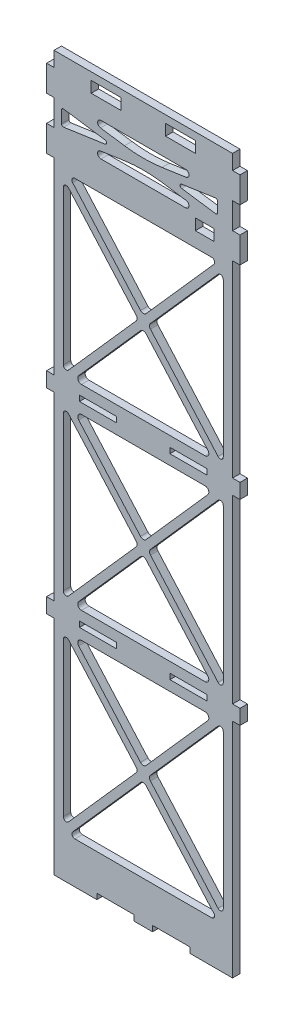
SolidWorks part; units mm, degrees
ref_plane "前视基准面" through (0, 0, 0) normal (0, 0, 1) x (1, 0, 0)
ref_plane "上视基准面" through (0, 0, 0) normal (0, 1, 0) x (1, 0, 0)
ref_plane "右视基准面" through (0, 0, 0) normal (1, 0, 0) x (0, 0, -1)
other "Configuration Table"
sketch "草图1" plane through (0, 0, 0) normal (0, 0, 1) x (1, 0, 0)
  line L0 (2263.2404, 1874.8927) -> (2311.2404, 1874.8927)
  line L1 (2313.2404, 1870.8927) -> (2313.2404, 1863.8927)
  line L2 (2313.2404, 1856.8927) -> (2313.2404, 1849.8927)
  line L3 (2313.2404, 1799.2927) -> (2313.2404, 1795.2927)
  line L4 (2313.2404, 1746.6927) -> (2313.2404, 1742.6927)
  line L5 (2263.2404, 1682.8927) -> (2274.7404, 1682.8927)
  line L6 (2284.7404, 1682.8927) -> (2289.7404, 1682.8927)
  line L7 (2299.7404, 1682.8927) -> (2311.2404, 1682.8927)
  line L8 (2261.2404, 1870.8927) -> (2261.2404, 1863.8927)
  line L9 (2261.2404, 1856.8927) -> (2261.2404, 1849.8927)
  line L10 (2311.2404, 1874.8927) -> (2311.2404, 1870.8927)
  line L11 (2311.2404, 1863.8927) -> (2311.2404, 1856.8927)
  line L12 (2313.2404, 1870.8927) -> (2311.2404, 1870.8927)
  line L13 (2313.2404, 1863.8927) -> (2311.2404, 1863.8927)
  line L14 (2313.2404, 1856.8927) -> (2311.2404, 1856.8927)
  line L15 (2313.2404, 1849.8927) -> (2311.2404, 1849.8927)
  line L16 (2313.2404, 1795.2927) -> (2311.2404, 1795.2927)
  line L17 (2311.2404, 1799.2927) -> (2313.2404, 1799.2927)
  line L18 (2311.2404, 1849.8927) -> (2311.2404, 1799.2927)
  line L19 (2313.2404, 1746.6927) -> (2311.2404, 1746.6927)
  line L20 (2311.2404, 1742.6927) -> (2313.2404, 1742.6927)
  line L21 (2311.2404, 1795.2927) -> (2311.2404, 1746.6927)
  line L22 (2311.2404, 1742.6927) -> (2311.2404, 1682.8927)
  line L23 (2263.2404, 1874.8927) -> (2263.2404, 1870.8927)
  line L24 (2263.2404, 1870.8927) -> (2261.2404, 1870.8927)
  line L25 (2261.2404, 1870.8927) -> (2261.2404, 1863.8927)
  line L26 (2261.2404, 1799.2927) -> (2261.2404, 1795.2927)
  line L27 (2261.2404, 1746.6927) -> (2261.2404, 1742.6927)
  line L28 (2263.2404, 1863.8927) -> (2263.2404, 1856.8927)
  line L29 (2261.2404, 1863.8927) -> (2263.2404, 1863.8927)
  line L30 (2261.2404, 1856.8927) -> (2263.2404, 1856.8927)
  line L31 (2261.2404, 1849.8927) -> (2263.2404, 1849.8927)
  line L32 (2261.2404, 1795.2927) -> (2263.2404, 1795.2927)
  line L33 (2263.2404, 1799.2927) -> (2261.2404, 1799.2927)
  line L34 (2263.2404, 1849.8927) -> (2263.2404, 1799.2927)
  line L35 (2261.2404, 1746.6927) -> (2263.2404, 1746.6927)
  line L36 (2263.2404, 1742.6927) -> (2261.2404, 1742.6927)
  line L37 (2263.2404, 1795.2927) -> (2263.2404, 1746.6927)
  line L38 (2263.2404, 1742.6927) -> (2263.2404, 1682.8927)
  line L39 (2305.6291, 1847.8927) -> (2287.2404, 1847.8927)
  line L40 (2306.2404, 1854.8927) -> (2301.2404, 1854.8927)
  line L41 (2306.2404, 1851.8927) -> (2301.2404, 1851.8927)
  line L42 (2268.8516, 1847.8927) -> (2305.6291, 1847.8927)
  line L43 (2268.8516, 1847.8927) -> (2275.4082, 1847.8927)
  line L44 (2299.0725, 1847.8927) -> (2305.6291, 1847.8927)
  line L45 (2305.3412, 1842.5418) -> (2289.1619, 1824.2554)
  line L46 (2286.4914, 1821.2371) -> (2269.8738, 1802.4554)
  line L47 (2306.2283, 1846.5626) -> (2290.985, 1829.3342)
  line L48 (2285.3188, 1822.9301) -> (2269.1395, 1804.6437)
  line L49 (2269.1395, 1842.5418) -> (2285.3188, 1824.2554)
  line L50 (2287.9893, 1821.2371) -> (2304.6069, 1802.4554)
  line L51 (2268.2524, 1846.5626) -> (2283.4957, 1829.3342)
  line L52 (2289.1619, 1822.9301) -> (2305.3412, 1804.6437)
  line L53 (2290.985, 1829.3342) -> (2290.1395, 1828.3785)
  line L54 (2283.4957, 1829.3342) -> (2284.3412, 1828.3785)
  line L55 (2290.1395, 1828.3785) -> (2287.9893, 1825.9483)
  line L56 (2286.4914, 1825.9483) -> (2284.3412, 1828.3785)
  line L57 (2265.7404, 1823.5927) -> (2265.7404, 1844.2721)
  line L58 (2269.1395, 1842.5418) -> (2267.1395, 1844.8022)
  line L59 (2265.7404, 1823.5927) -> (2265.7404, 1802.9133)
  line L60 (2269.1395, 1804.6437) -> (2267.1395, 1802.3832)
  line L61 (2308.7404, 1823.5927) -> (2308.7404, 1844.2721)
  line L62 (2308.7404, 1823.5927) -> (2308.7404, 1802.9133)
  line L63 (2305.3412, 1842.5418) -> (2307.3412, 1844.8022)
  line L64 (2305.3412, 1804.6437) -> (2307.3412, 1802.3832)
  line L65 (2294.3985, 1796.5427) -> (2294.3985, 1797.2927)
  line L66 (2294.3985, 1797.2927) -> (2294.3985, 1798.0427)
  line L67 (2304.3985, 1798.0427) -> (2304.3985, 1796.5427)
  line L68 (2294.3985, 1797.2927) -> (2294.3985, 1798.0427)
  line L69 (2294.3985, 1798.0427) -> (2304.3985, 1798.0427)
  line L70 (2294.3985, 1796.5427) -> (2304.3985, 1796.5427)
  line L71 (2280.0822, 1796.5427) -> (2280.0822, 1797.2927)
  line L72 (2280.0822, 1797.2927) -> (2280.0822, 1798.0427)
  line L73 (2270.0822, 1798.0427) -> (2270.0822, 1796.5427)
  line L74 (2280.0822, 1797.2927) -> (2280.0822, 1798.0427)
  line L75 (2280.0822, 1798.0427) -> (2270.0822, 1798.0427)
  line L76 (2280.0822, 1796.5427) -> (2270.0822, 1796.5427)
  line L77 (2294.3985, 1798.0427) -> (2294.3985, 1797.2927)
  line L78 (2305.3412, 1789.9418) -> (2289.1619, 1771.6554)
  line L79 (2286.4914, 1768.6371) -> (2269.8738, 1749.8554)
  line L80 (2304.6069, 1792.1301) -> (2290.985, 1776.7342)
  line L81 (2285.3188, 1770.3301) -> (2269.1395, 1752.0437)
  line L82 (2269.1395, 1789.9418) -> (2285.3188, 1771.6554)
  line L83 (2287.9893, 1768.6371) -> (2304.6069, 1749.8554)
  line L84 (2269.8738, 1792.1301) -> (2283.4957, 1776.7342)
  line L85 (2289.1619, 1770.3301) -> (2305.3412, 1752.0437)
  line L86 (2290.985, 1776.7342) -> (2290.1395, 1775.7785)
  line L87 (2283.4957, 1776.7342) -> (2284.3412, 1775.7785)
  line L88 (2290.1395, 1775.7785) -> (2287.9893, 1773.3483)
  line L89 (2286.4914, 1773.3483) -> (2284.3412, 1775.7785)
  line L90 (2265.7404, 1770.9927) -> (2265.7404, 1791.6721)
  line L91 (2269.1395, 1789.9418) -> (2267.1395, 1792.2022)
  line L92 (2265.7404, 1770.9927) -> (2265.7404, 1750.3133)
  line L93 (2269.1395, 1752.0437) -> (2267.1395, 1749.7832)
  line L94 (2308.7404, 1770.9927) -> (2308.7404, 1791.6721)
  line L95 (2308.7404, 1770.9927) -> (2308.7404, 1750.3133)
  line L96 (2305.3412, 1789.9418) -> (2307.3412, 1792.2022)
  line L97 (2305.3412, 1752.0437) -> (2307.3412, 1749.7832)
  line L98 (2294.3985, 1745.4427) -> (2294.3985, 1744.6927)
  line L99 (2294.3985, 1744.6927) -> (2294.3985, 1743.9427)
  line L100 (2304.3985, 1743.9427) -> (2304.3985, 1745.4427)
  line L101 (2294.3985, 1744.6927) -> (2294.3985, 1743.9427)
  line L102 (2294.3985, 1743.9427) -> (2304.3985, 1743.9427)
  line L103 (2294.3985, 1745.4427) -> (2304.3985, 1745.4427)
  line L104 (2280.0822, 1745.4427) -> (2280.0822, 1744.6927)
  line L105 (2280.0822, 1744.6927) -> (2280.0822, 1743.9427)
  line L106 (2270.0822, 1743.9427) -> (2270.0822, 1745.4427)
  line L107 (2280.0822, 1744.6927) -> (2280.0822, 1743.9427)
  line L108 (2280.0822, 1743.9427) -> (2270.0822, 1743.9427)
  line L109 (2280.0822, 1745.4427) -> (2270.0822, 1745.4427)
  line L110 (2294.3985, 1743.9427) -> (2294.3985, 1744.6927)
  line L111 (2287.2404, 1694.0927) -> (2305.6291, 1694.0927)
  line L112 (2287.2404, 1694.0927) -> (2268.8516, 1694.0927)
  line L113 (2305.3412, 1737.3418) -> (2289.1619, 1719.0554)
  line L114 (2286.4914, 1716.0371) -> (2268.2524, 1695.4228)
  line L115 (2304.6069, 1739.5301) -> (2290.985, 1724.1342)
  line L116 (2285.3188, 1717.7301) -> (2269.1395, 1699.4437)
  line L117 (2269.1395, 1737.3418) -> (2285.3188, 1719.0554)
  line L118 (2287.9893, 1716.0371) -> (2306.2283, 1695.4228)
  line L119 (2269.8738, 1739.5301) -> (2283.4957, 1724.1342)
  line L120 (2289.1619, 1717.7301) -> (2305.3412, 1699.4437)
  line L121 (2290.985, 1724.1342) -> (2290.1395, 1723.1785)
  line L122 (2283.4957, 1724.1342) -> (2284.3412, 1723.1785)
  line L123 (2290.1395, 1723.1785) -> (2287.9893, 1720.7483)
  line L124 (2286.4914, 1720.7483) -> (2284.3412, 1723.1785)
  line L125 (2265.7404, 1718.3927) -> (2265.7404, 1739.0721)
  line L126 (2269.1395, 1737.3418) -> (2267.1395, 1739.6022)
  line L127 (2265.7404, 1718.3927) -> (2265.7404, 1697.7133)
  line L128 (2269.1395, 1699.4437) -> (2267.1395, 1697.1832)
  line L129 (2308.7404, 1718.3927) -> (2308.7404, 1739.0721)
  line L130 (2308.7404, 1718.3927) -> (2308.7404, 1697.7133)
  line L131 (2305.3412, 1737.3418) -> (2307.3412, 1739.6022)
  line L132 (2305.3412, 1699.4437) -> (2307.3412, 1697.1832)
  line L133 (2289.7404, 1682.8927) -> (2289.7404, 1683.6427)
  line L134 (2289.7404, 1683.6427) -> (2289.7404, 1684.3927)
  line L135 (2299.7404, 1684.3927) -> (2299.7404, 1682.8927)
  line L136 (2289.7404, 1683.6427) -> (2289.7404, 1684.3927)
  line L137 (2289.7404, 1684.3927) -> (2299.7404, 1684.3927)
  line L138 (2284.7404, 1682.8927) -> (2284.7404, 1683.6427)
  line L139 (2274.7404, 1684.3927) -> (2274.7404, 1682.8927)
  line L140 (2284.7404, 1684.3927) -> (2274.7404, 1684.3927)
  line L141 (2289.7404, 1684.3927) -> (2289.7404, 1683.6427)
  line L142 (2284.7404, 1684.3927) -> (2284.7404, 1683.6427)
  line L143 (2293.2404, 1872.8927) -> (2293.2404, 1869.8927)
  line L144 (2293.2404, 1872.8927) -> (2301.2404, 1872.8927)
  line L145 (2301.2404, 1872.8927) -> (2301.2404, 1869.8927)
  line L146 (2301.2404, 1869.8927) -> (2293.2404, 1869.8927)
  line L147 (2281.2404, 1872.8927) -> (2281.2404, 1869.8927)
  line L148 (2281.2404, 1872.8927) -> (2273.2404, 1872.8927)
  line L149 (2273.2404, 1872.8927) -> (2273.2404, 1869.8927)
  line L150 (2273.2404, 1869.8927) -> (2281.2404, 1869.8927)
  line L151 (2301.2404, 1854.8927) -> (2301.2404, 1851.8927)
  line L152 (2301.2404, 1851.8927) -> (2306.2404, 1851.8927)
  line L153 (2301.2404, 1851.8927) -> (2306.2404, 1851.8927)
  line L154 (2306.2404, 1851.8927) -> (2306.2404, 1854.8927)
  line L155 (2265.8116, 1862.5072) -> (2276.9187, 1860.8874)
  line L156 (2292.2911, 1858.6456) -> (2298.7445, 1857.7045)
  line L157 (2275.7363, 1863.081) -> (2282.1896, 1862.1399)
  line L158 (2297.5627, 1859.898) -> (2306.6682, 1858.5701)
  line L159 (2265.8125, 1858.2784) -> (2276.9187, 1859.8981)
  line L160 (2292.2911, 1862.1399) -> (2298.7445, 1863.081)
  line L161 (2263.3834, 1855.903) -> (2263.3866, 1855.9035)
  line L162 (2275.7353, 1857.7043) -> (2282.1896, 1858.6456)
  line L163 (2297.5627, 1860.8875) -> (2306.6682, 1862.2154)
  line L164 (2265.2404, 1862.0123) -> (2265.2404, 1858.7732)
  line L165 (2298.6138, 1864.882) -> (2275.8669, 1864.882)
  line L166 (2298.6138, 1855.9035) -> (2275.8669, 1855.9035)
  line L167 (2307.2404, 1861.7206) -> (2307.2404, 1859.0648)
  line L168 (2287.2404, 1793.7927) -> (2303.858, 1793.7927)
  line L169 (2287.2404, 1793.7927) -> (2270.6227, 1793.7927)
  line L170 (2287.2404, 1748.1927) -> (2303.858, 1748.1927)
  line L171 (2287.2404, 1748.1927) -> (2270.6227, 1748.1927)
  line L172 (2287.2404, 1741.1927) -> (2303.858, 1741.1927)
  line L173 (2287.2404, 1741.1927) -> (2270.6227, 1741.1927)
  line L174 (2287.2404, 1800.7927) -> (2303.858, 1800.7927)
  line L175 (2287.2404, 1800.7927) -> (2270.6227, 1800.7927)
  arc A0 (2306.2283, 1846.5626) -> (2305.6291, 1847.8927) centre (2305.6291, 1847.0927) ccw
  arc A1 (2289.1619, 1824.2554) -> (2289.1619, 1822.9301) centre (2289.9108, 1823.5927) ccw
  arc A2 (2286.4914, 1825.9483) -> (2287.9893, 1825.9483) centre (2287.2404, 1826.6109) ccw
  arc A3 (2285.3188, 1822.9301) -> (2285.3188, 1824.2554) centre (2284.5699, 1823.5927) ccw
  arc A4 (2268.8516, 1847.8927) -> (2268.2524, 1846.5626) centre (2268.8516, 1847.0927) ccw
  arc A5 (2287.9893, 1821.2371) -> (2286.4914, 1821.2371) centre (2287.2404, 1820.5745) ccw
  arc A6 (2267.1395, 1844.8022) -> (2265.7404, 1844.2721) centre (2266.5404, 1844.2721) ccw
  arc A7 (2265.7404, 1802.9133) -> (2267.1395, 1802.3832) centre (2266.5404, 1802.9133) ccw
  arc A8 (2308.7404, 1844.2721) -> (2307.3412, 1844.8022) centre (2307.9404, 1844.2721) ccw
  arc A9 (2307.3412, 1802.3832) -> (2308.7404, 1802.9133) centre (2307.9404, 1802.9133) ccw
  arc A10 (2289.1619, 1771.6554) -> (2289.1619, 1770.3301) centre (2289.9108, 1770.9927) ccw
  arc A11 (2286.4914, 1773.3483) -> (2287.9893, 1773.3483) centre (2287.2404, 1774.0109) ccw
  arc A12 (2285.3188, 1770.3301) -> (2285.3188, 1771.6554) centre (2284.5699, 1770.9927) ccw
  arc A13 (2287.9893, 1768.6371) -> (2286.4914, 1768.6371) centre (2287.2404, 1767.9745) ccw
  arc A14 (2267.1395, 1792.2022) -> (2265.7404, 1791.6721) centre (2266.5404, 1791.6721) ccw
  arc A15 (2265.7404, 1750.3133) -> (2267.1395, 1749.7832) centre (2266.5404, 1750.3133) ccw
  arc A16 (2308.7404, 1791.6721) -> (2307.3412, 1792.2022) centre (2307.9404, 1791.6721) ccw
  arc A17 (2307.3412, 1749.7832) -> (2308.7404, 1750.3133) centre (2307.9404, 1750.3133) ccw
  arc A18 (2289.1619, 1719.0554) -> (2289.1619, 1717.7301) centre (2289.9108, 1718.3927) ccw
  arc A19 (2286.4914, 1720.7483) -> (2287.9893, 1720.7483) centre (2287.2404, 1721.4109) ccw
  arc A20 (2285.3188, 1717.7301) -> (2285.3188, 1719.0554) centre (2284.5699, 1718.3927) ccw
  arc A21 (2305.6291, 1694.0927) -> (2306.2283, 1695.4228) centre (2305.6291, 1694.8927) ccw
  arc A22 (2268.2524, 1695.4228) -> (2268.8516, 1694.0927) centre (2268.8516, 1694.8927) ccw
  arc A23 (2287.9893, 1716.0371) -> (2286.4914, 1716.0371) centre (2287.2404, 1715.3745) ccw
  arc A24 (2267.1395, 1739.6022) -> (2265.7404, 1739.0721) centre (2266.5404, 1739.0721) ccw
  arc A25 (2265.7404, 1697.7133) -> (2267.1395, 1697.1832) centre (2266.5404, 1697.7133) ccw
  arc A26 (2308.7404, 1739.0721) -> (2307.3412, 1739.6022) centre (2307.9404, 1739.0721) ccw
  arc A27 (2307.3412, 1697.1832) -> (2308.7404, 1697.7133) centre (2307.9404, 1697.7133) ccw
  arc A28 (2297.5627, 1860.8875) -> (2297.5627, 1859.898) centre (2297.6349, 1860.3927) ccw
  arc A29 (2292.2911, 1858.6456) -> (2282.1896, 1858.6456) centre (2287.2404, 1824.0119) ccw
  arc A30 (2307.2404, 1861.7206) -> (2306.6682, 1862.2154) centre (2306.7404, 1861.7206) ccw
  arc A31 (2276.9187, 1859.8981) -> (2276.918, 1860.8875) centre (2276.8459, 1860.3927) ccw
  arc A32 (2282.1896, 1862.1399) -> (2292.2911, 1862.1399) centre (2287.2404, 1896.7735) ccw
  arc A33 (2265.2404, 1858.7732) -> (2265.8125, 1858.2784) centre (2265.7404, 1858.7732) ccw
  arc A34 (2265.8116, 1862.5072) -> (2265.2404, 1862.0123) centre (2265.7404, 1862.0123) ccw
  arc A35 (2298.7445, 1863.081) -> (2298.6138, 1864.882) centre (2298.6138, 1863.9767) ccw
  arc A36 (2298.6138, 1855.9035) -> (2298.7445, 1857.7045) centre (2298.6138, 1856.8087) ccw
  arc A37 (2275.8669, 1864.882) -> (2275.7363, 1863.081) centre (2275.8669, 1863.9767) ccw
  arc A38 (2275.7353, 1857.7043) -> (2275.8669, 1855.9035) centre (2275.8669, 1856.8087) ccw
  arc A39 (2306.6682, 1858.5701) -> (2307.2404, 1859.0648) centre (2306.7404, 1859.0648) ccw
  arc A40 (2304.6069, 1792.1301) -> (2303.858, 1793.7927) centre (2303.858, 1792.7927) ccw
  arc A41 (2270.6227, 1793.7927) -> (2269.8738, 1792.1301) centre (2270.6227, 1792.7927) ccw
  arc A42 (2303.858, 1748.1927) -> (2304.6069, 1749.8554) centre (2303.858, 1749.1927) ccw
  arc A43 (2269.8738, 1749.8554) -> (2270.6227, 1748.1927) centre (2270.6227, 1749.1927) ccw
  arc A44 (2304.6069, 1739.5301) -> (2303.858, 1741.1927) centre (2303.858, 1740.1927) ccw
  arc A45 (2270.6227, 1741.1927) -> (2269.8738, 1739.5301) centre (2270.6227, 1740.1927) ccw
  arc A46 (2303.858, 1800.7927) -> (2304.6069, 1802.4554) centre (2303.858, 1801.7927) ccw
  arc A47 (2269.8738, 1802.4554) -> (2270.6227, 1800.7927) centre (2270.6227, 1801.7927) ccw
extrude "凸台-拉伸1" add sketch "草图1" along normal blind 2
